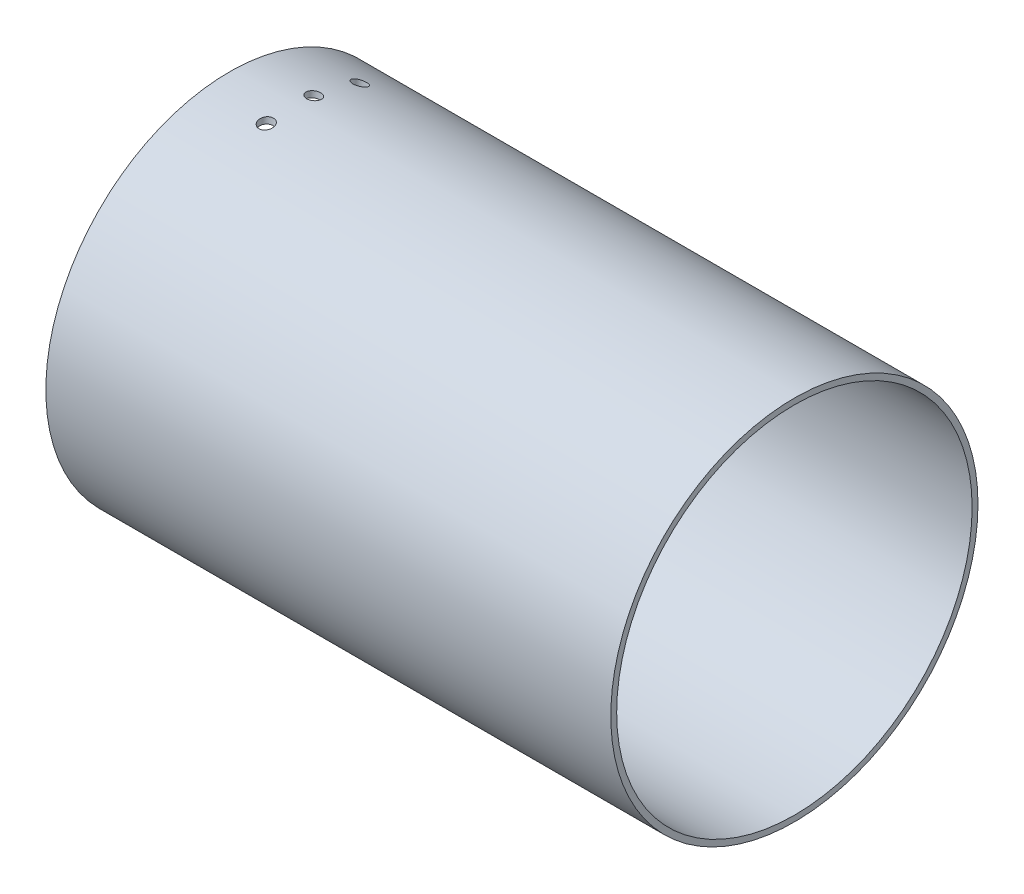
SolidWorks part; units mm, degrees
material "E-Glass Fiber"
ref_plane "Front Plane" through (0, 0, 0) normal (0, 0, 1) x (1, 0, 0)
ref_plane "Top Plane" through (0, 0, 0) normal (0, 1, 0) x (1, 0, 0)
ref_plane "Right Plane" through (0, 0, 0) normal (1, 0, 0) x (0, 0, -1)
sketch "Sketch1" plane through (0, 0, 0) normal (1, 0, 0) x (0, 0, -1)
  circle A0 centre (0, 0) radius 49.53
  circle A1 centre (0, 0) radius 47.9425
  dimension "D1" = 99.06
  dimension "D2" = 1.5875
extrude "Boss-Extrude1" add sketch "Sketch1" along normal blind 152.4
sketch "Sketch2" plane through (-485.2598, 0, 0) normal (0, 0.9921, -0.1252) x (0, 0.1252, 0.9921)
  circle A0 centre (12.7, 501.8015) radius 1.905
  circle A1 centre (0, 501.8015) radius 1.905
  circle A2 centre (-12.7, 501.8015) radius 1.905
  circle A4 centre (-12.7, 501.8015) radius 1.905 construction
  circle A5 centre (0, 501.8015) radius 1.905 construction
  circle A6 centre (12.7, 501.8015) radius 1.905 construction
extrude "Cut-Extrude1" cut sketch "Sketch2" against normal through all and the other way through all
